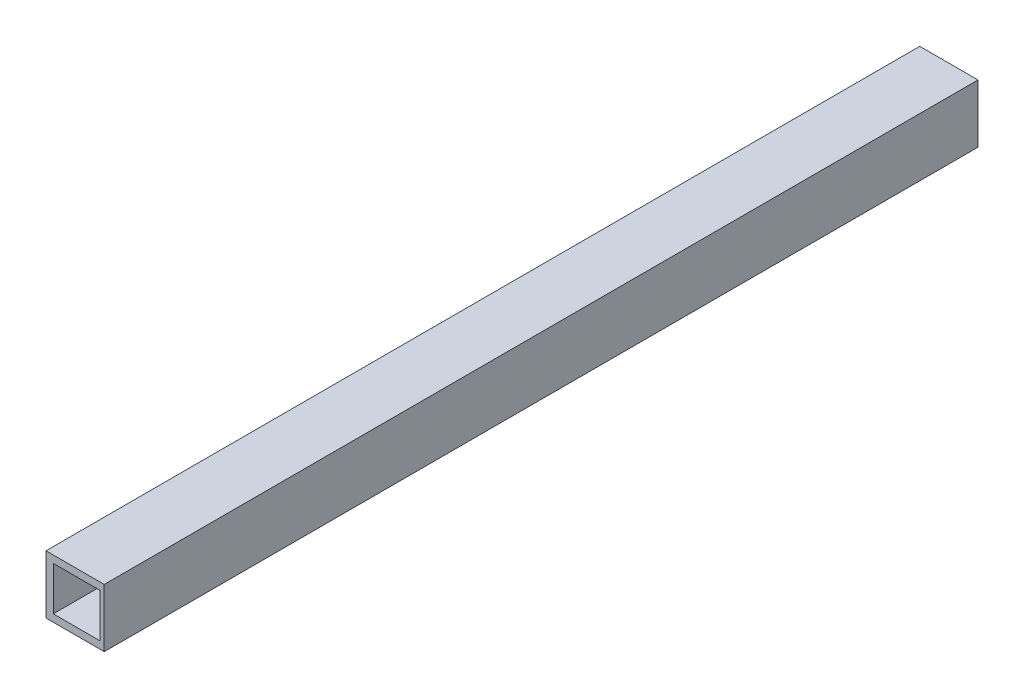
SolidWorks part; units mm, degrees
ref_plane "Front Plane" through (0, 0, 0) normal (0, 0, 1) x (1, 0, 0)
ref_plane "Top Plane" through (0, 0, 0) normal (0, 1, 0) x (1, 0, 0)
ref_plane "Right Plane" through (0, 0, 0) normal (1, 0, 0) x (0, 0, -1)
sketch "Sketch1" plane through (0, 0, 0) normal (0, 0, 1) x (1, 0, 0)
  line L1 (0, 0) -> (25.4, 0)
  line L2 (0, 0) -> (0, 25.4)
  line L3 (0, 25.4) -> (25.4, 25.4)
  line L4 (25.4, 0) -> (25.4, 25.4)
  dimension "D1" = 25.4
  dimension "D2" = 25.4
extrude "Boss-Extrude2" add sketch "Sketch1" along normal blind 381 contours L3 L4 L1 L2
sketch "Sketch2" plane through (0, 0, 0) normal (0, 0, -1) x (-1, 0, 0)
  line L0 (-23.4778, 22.225) -> (-3.175, 22.225)
  line L1 (-23.4778, 22.225) -> (-23.4778, 3.175)
  line L2 (-23.4778, 3.175) -> (-3.175, 3.175)
  line L3 (-3.175, 22.225) -> (-3.175, 3.175)
  line L4 (0, 0) -> (0, 25.4) construction
  line L5 (0, 0) -> (-25.4, 0) construction
  dimension "D1" = 3.175
  dimension "D2" = 3.175
extrude "Cut-Extrude1" cut sketch "Sketch2" against normal through all
